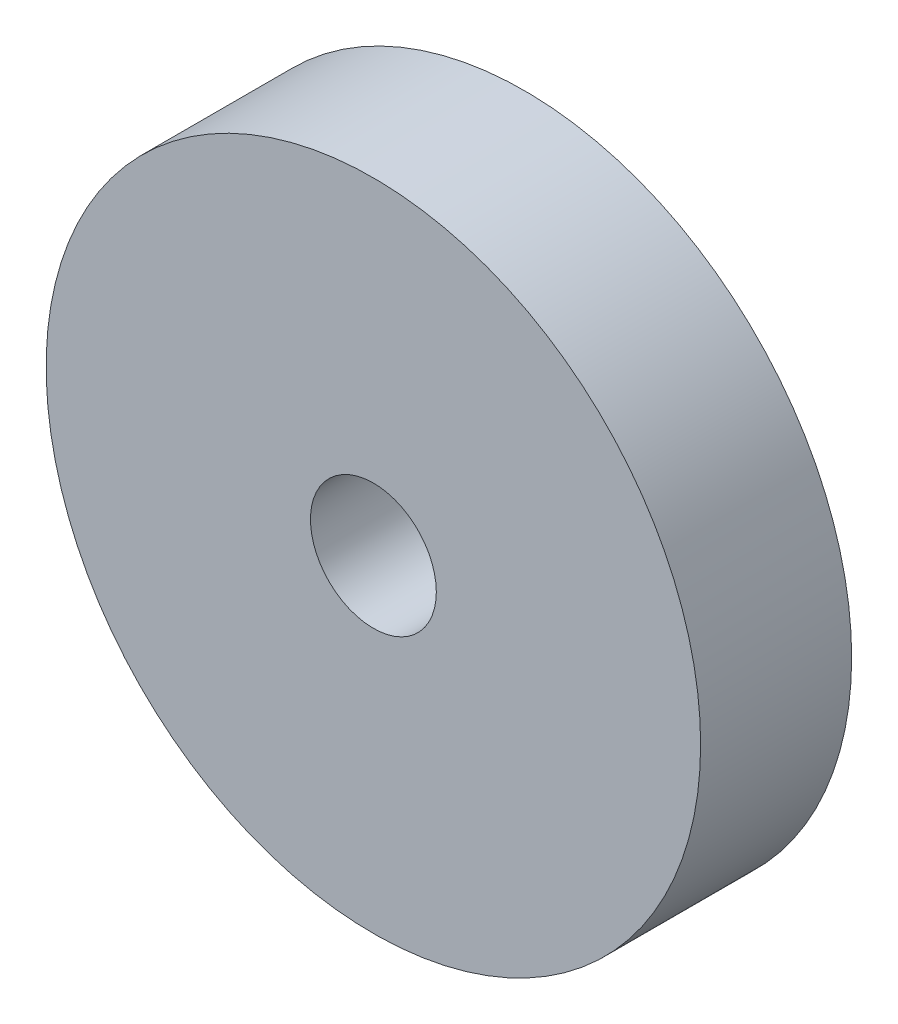
SolidWorks part; units mm, degrees
ref_plane "前视基准面" through (0, 0, 0) normal (0, 0, 1) x (1, 0, 0)
ref_plane "上视基准面" through (0, 0, 0) normal (0, 1, 0) x (1, 0, 0)
ref_plane "右视基准面" through (0, 0, 0) normal (1, 0, 0) x (0, 0, -1)
other "Configuration Table"
sketch "草图1" plane through (0, 0, 0) normal (0, 0, 1) x (1, 0, 0)
  circle A0 centre (0, 0) radius 6.5
  circle A1 centre (0, 0) radius 1.25
  dimension "D1" = 13
  dimension "D2" = 2.5
extrude "凸台-拉伸1" add sketch "草图1" along normal blind 3
